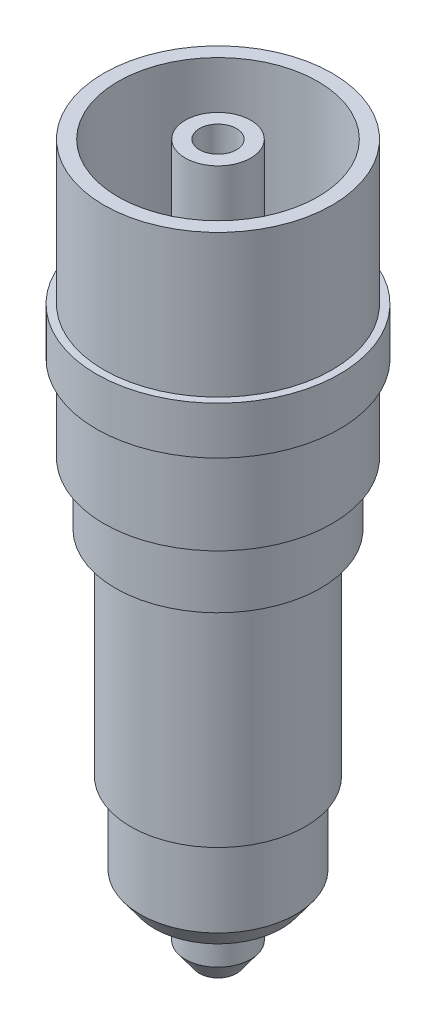
SolidWorks part; units mm, degrees
ref_plane "Front Plane" through (0, 0, 0) normal (0, 0, 1) x (1, 0, 0)
ref_plane "Top Plane" through (0, 0, 0) normal (0, 1, 0) x (1, 0, 0)
ref_plane "Right Plane" through (0, 0, 0) normal (1, 0, 0) x (0, 0, -1)
sketch "Sketch1" plane through (0, 0, 0) normal (0, 0, 1) x (1, 0, 0)
  line L0 (0, 0) -> (0, 30) construction
  line L1 (0, -82.5) -> (0, 82.5) construction
  line L2 (0, 30) -> (-20.1312, 30) construction
  line L3 (-20.1312, 30) -> (-20.1312, 0) construction
  line L4 (14.0645, 0) -> (-14.0645, 0) construction
  line L6 (-20.1312, 30) -> (-20.1312, 0)
  line L10 (-21.6855, 0) -> (-20.1312, 0)
  line L11 (-21.6855, 0) -> (-21.6855, -10)
  line L12 (-21.6855, -10) -> (-20.1312, -10)
  line L14 (-20.1312, -10) -> (-20.1312, -28)
  line L15 (-20.1312, -28) -> (-17.6791, -28)
  line L16 (0, 30) -> (3.8864, 30) construction
  line L17 (-17.6791, -28) -> (-17.6791, -41)
  line L18 (-17.6791, -41) -> (-14.4878, -41)
  line L19 (3.8864, 30) -> (3.8864, -87.5) construction
  line L20 (-14.4878, -41) -> (-14.4878, -86)
  line L21 (-14.4878, -86) -> (-12.4668, -86)
  line L22 (3.8864, -87.5) -> (0, -87.5) construction
  line L23 (-12.4668, -86) -> (-12.4668, -103)
  line L25 (0, 30) -> (0, -120)
  line L28 (-3, 27) -> (-3, -110.8361)
  line L30 (-9.4668, -83) -> (-9.4668, -102.0179)
  line L31 (-11.4878, -83) -> (-9.4668, -83)
  line L32 (-11.4878, -38) -> (-11.4878, -83)
  line L33 (-14.6791, -38) -> (-11.4878, -38)
  line L34 (-14.6791, -25) -> (-14.6791, -38)
  line L35 (-17.1312, -25) -> (-14.6791, -25)
  line L36 (-17.1312, -7) -> (-17.1312, -25)
  line L37 (-18.6855, -7) -> (-17.1312, -7)
  line L38 (-18.6855, -3) -> (-18.6855, -7)
  line L39 (-18.6855, -3) -> (-17.1312, -3)
  line L40 (-17.1312, 27) -> (-17.1312, -3)
  line L42 (-3, 27) -> (-17.1312, 27) construction
  line L43 (-17.1312, 27) -> (-17.1312, 30)
  line L44 (-3, 27) -> (-3, 30)
  line L45 (-20.1312, 30) -> (-17.1312, 30)
  line L46 (0, 30) -> (-20.1312, 30) construction
  line L47 (-3, 30) -> (0, 30)
  line L48 (-9.4668, -102.0179) -> (-9.4668, -107.0909)
  line L49 (-3, -110.8361) -> (-3, -115.9091)
  line L50 (-12.4668, -103) -> (-9.4668, -107.0909)
  line L51 (-3, -110.8361) -> (-9.4668, -102.0179) construction
  line L52 (0, -120) -> (-12.4668, -103) construction
  line L53 (-3, -115.9091) -> (0, -120)
  dimension "D1" = 45
  dimension "D2" = 30
  dimension "D3" = 10
  dimension "D4" = 18
  dimension "D5" = 13
  dimension "D6" = 45
  dimension "D7" = 17
  dimension "D8" = 3
  dimension "D9" = 117.5
revolve "Revolve8" add sketch "Sketch1" angle 360 about L19
